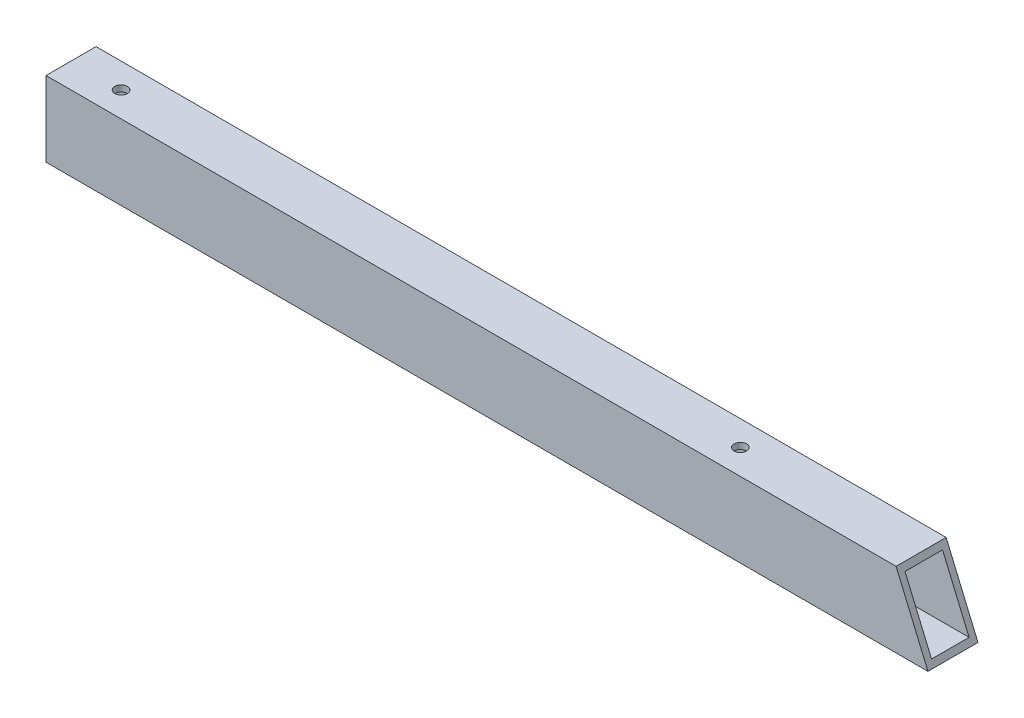
SolidWorks part; units mm, degrees
ref_plane "Front Plane" through (0, 0, 0) normal (0, 0, 1) x (1, 0, 0)
ref_plane "Top Plane" through (0, 0, 0) normal (0, 1, 0) x (1, 0, 0)
ref_plane "Right Plane" through (0, 0, 0) normal (1, 0, 0) x (0, 0, -1)
sketch "Sketch1" plane through (0, 0, 0) normal (1, 0, 0) x (0, 0, -1)
  line L1 (-12.7, 19.05) -> (12.7, 19.05)
  line L2 (-12.7, 19.05) -> (-12.7, -19.05)
  line L3 (-12.7, -19.05) -> (12.7, -19.05)
  line L4 (12.7, 19.05) -> (12.7, -19.05)
  line L5 (-12.7, 19.05) -> (12.7, -19.05) construction
  line L6 (-12.7, -19.05) -> (12.7, 19.05) construction
  point P0 (0, 0)
  dimension "height" = 38.1
  dimension "width" = 25.4
extrude "beam" add sketch "Sketch1" against normal blind 447.675 thin
sketch "Sketch2" plane through (0, 0, 12.7) normal (0, 0, 1) x (1, 0, 0)
  line L0 (0, -19.05) -> (-16.1725, 19.05)
  line L1 (-447.675, 19.05) -> (0, 19.05) construction
  line L2 (-16.1725, 19.05) -> (0, 19.05)
  line L3 (0, 19.05) -> (0, -19.05)
  dimension "mitre angle" = 23
extrude "miter cut" cut sketch "Sketch2" against normal through all
sketch "Sketch3" plane through (0, 0, 12.7) normal (0, 0, 1) x (1, 0, 0)
  line L0 (-447.675, 19.05) -> (-447.675, -19.05) construction
  line L1 (-447.675, 19.05) -> (-16.1725, 19.05) construction
  circle A0 centre (-422.275, 4.7625) radius 11.1125
  dimension "axle hole diameter" = 22.225
  dimension "axle hole distance from end" = 25.4
  dimension "axle hole distance from top" = 14.2875
extrude "axle shaft hole!" [suppressed] cut sketch "Sketch3" against normal through all
sketch "Sketch4" plane through (0, 19.05, 0) normal (0, 1, 0) x (1, 0, 0)
  line L0 (-447.675, 0) -> (-16.1725, 0) construction
  line L1 (-447.675, 12.7) -> (-447.675, -12.7) construction
  line L2 (-16.1725, 12.7) -> (-16.1725, -12.7) construction
  circle A0 centre (-422.275, 0) radius 3.175
  circle A1 centre (-107.95, 0) radius 3.175
  dimension "bolt hole diameter" = 6.35
  dimension "first bolt from end" = 25.4
  dimension "bolt hole spacing" = 314.325
extrude "bolt clearance hole" cut sketch "Sketch4" against normal through all
sketch "Sketch5" plane through (0, -19.05, 0) normal (0, -1, 0) x (1, 0, 0)
  circle A0 centre (-422.275, 0) radius 6.35
  circle A1 centre (-107.95, 0) radius 6.35
  dimension "clearance hole diameter" = 12.7
extrude "clearance hole" cut sketch "Sketch5" against normal blind 12.7
